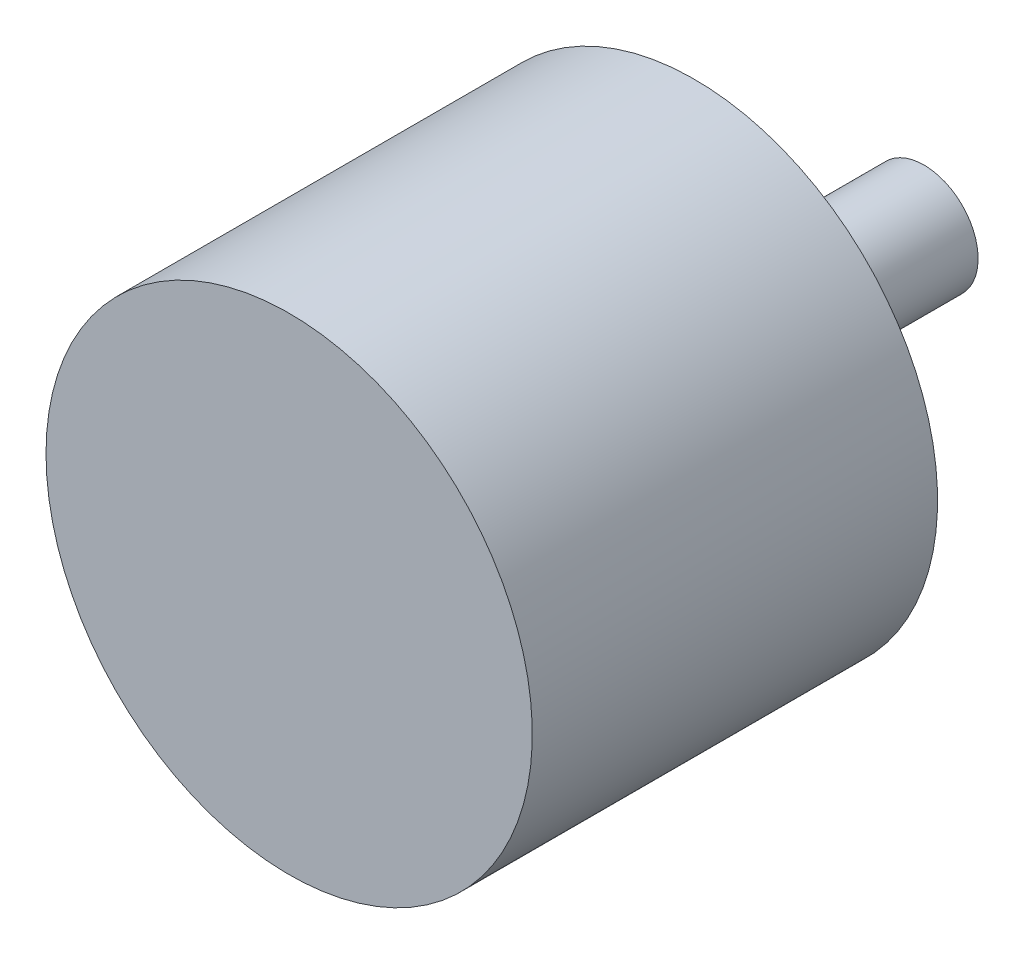
SolidWorks part; units mm, degrees
ref_plane "Front Plane" through (0, 0, 0) normal (0, 0, 1) x (1, 0, 0)
ref_plane "Top Plane" through (0, 0, 0) normal (0, 1, 0) x (1, 0, 0)
ref_plane "Right Plane" through (0, 0, 0) normal (1, 0, 0) x (0, 0, -1)
ref_plane "Plane1" through (0, 0, 0) normal (0, 0, 1) x (1, 0, 0)
ref_plane "Plane2" through (0, 0, 0) normal (0, -1, 0) x (1, 0, 0)
sketch "Sketch2" plane through (0, 0, 0) normal (0, -1, 0) x (1, 0, 0)
  line L0 (18, 30) -> (0, 30)
  line L1 (0, 30) -> (0, -17)
  line L2 (0, -17) -> (4, -17)
  line L3 (4, -17) -> (4, 0)
  line L4 (4, 0) -> (18, 0)
  line L5 (18, 0) -> (18, 30)
  line L6 (0, 30) -> (0, -17) construction
revolve "Revolve1" add sketch "Sketch2" angle 360 about L6
hole_wizard "Ø3.5 (3.5) Diameter Hole1" positions "Sketch4" profile "Sketch3" hole size "Ø3.5" standard "ANSI Metric"
sketch "Sketch4" plane through (0, 0, 0) normal (0, 0, -1) x (-1, 0, 0)
  point P0 (9.8995, 9.8995)
  point P1 (-9.8995, -9.8995)
  point P2 (9.8995, -9.8995)
  point P3 (-9.8995, 9.8995)
sketch "Sketch3" plane through (-9.8995, 9.8995, 0) normal (1, 0, 0) x (0, 1, 0)
  line L0 (0, 0) -> (0, 5)
  line L1 (0, 5) -> (1.75, 5)
  line L2 (1.75, 5) -> (1.75, 0)
  line L5 (1.75, 0) -> (0, 0)
  line L10 (0, 5) -> (-1.75, 5) construction
  line L11 (0, -6.35) -> (0, 107.95) construction
  dimension "Hole Dia." = 3.5
  dimension "Hole Depth" = 5
  dimension "Drill Angle" = 180
